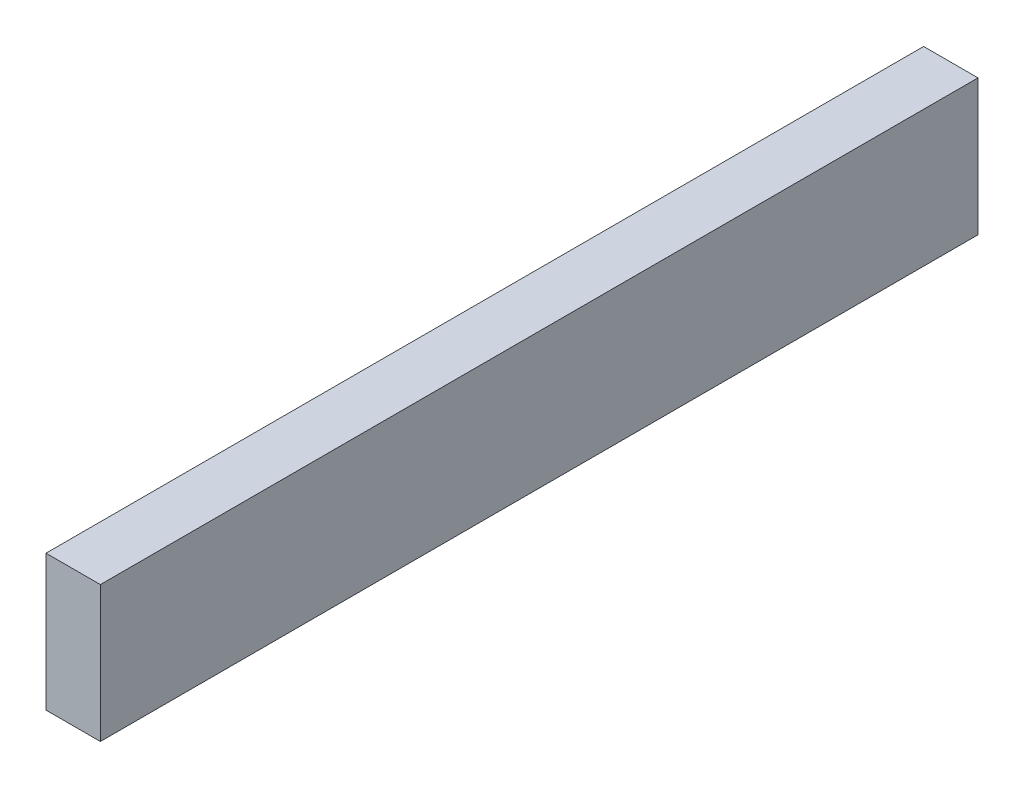
SolidWorks part; units mm, degrees
material "Low Carbon Steel"
ref_plane "Front Plane" through (0, 0, 0) normal (0, 0, 1) x (1, 0, 0)
ref_plane "Top Plane" through (0, 0, 0) normal (0, 1, 0) x (1, 0, 0)
ref_plane "Right Plane" through (0, 0, 0) normal (1, 0, 0) x (0, 0, -1)
sketch "Sketch1" plane through (0, 0, 0) normal (0, 0, 1) x (1, 0, 0)
  line L1 (0, 0) -> (50.8, 0)
  line L2 (0, 0) -> (0, 127)
  line L3 (0, 127) -> (50.8, 127)
  line L4 (50.8, 0) -> (50.8, 127)
  dimension "D1" = 50.8
  dimension "D2" = 127
extrude "Boss-Extrude1" add sketch "Sketch1" along normal blind 820
other "Freeze***"
